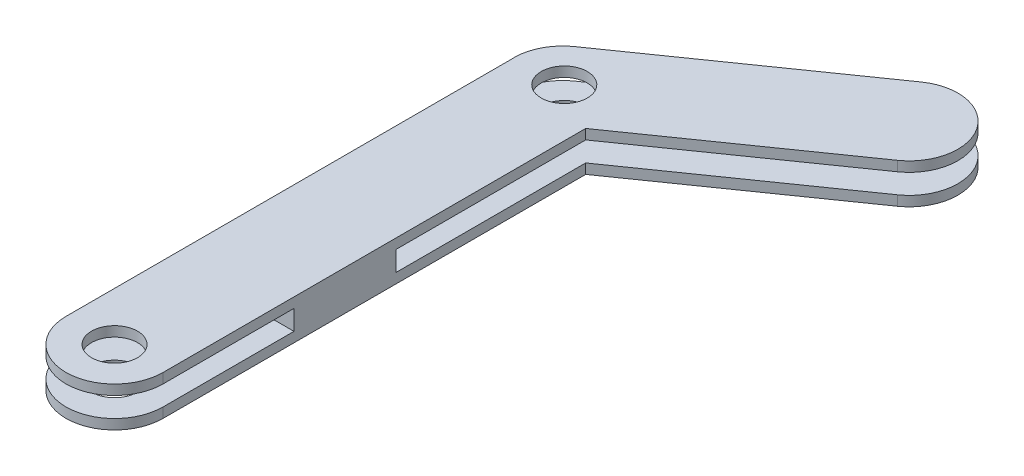
SolidWorks part; units mm, degrees
ref_plane "前视基准面" through (0, 0, 0) normal (0, 0, 1) x (1, 0, 0)
ref_plane "上视基准面" through (0, 0, 0) normal (0, 1, 0) x (1, 0, 0)
ref_plane "右视基准面" through (0, 0, 0) normal (1, 0, 0) x (0, 0, -1)
other "Configuration Table"
sketch "草图2" plane through (0, 0, 0) normal (0, 1, 0) x (1, 0, 0)
  line L0 (0, 0) -> (0, 180) construction
  line L1 (-19.5, 0) -> (-19.5, 180)
  line L2 (19.5, 0) -> (19.5, 180)
  arc A0 (-19.5, 0) -> (19.5, 0) centre (0, 0) ccw
  arc A1 (19.5, 180) -> (-19.5, 180) centre (0, 180) ccw
  point P3 (0, 90)
  dimension "D1" = 180
extrude "凸台-拉伸1" add sketch "草图2" along normal blind 4
sketch "草图3" plane through (0, 4, 0) normal (0, 1, 0) x (-1, 0, 0)
  line L0 (0, 0) -> (0, -180) construction
  circle A0 centre (0, -180) radius 9.2428
  circle A1 centre (0, 0) radius 9.2428
extrude "切除-拉伸2" cut sketch "草图3" against normal blind 8
sketch "草图5" plane through (0, 0, 0) normal (0, 1, 0) x (1, 0, 0)
  line L0 (-19.5, 180) -> (-19.5, 0) construction
  line L1 (-19.5, 93.4928) -> (19.5, 93.4928)
  line L2 (-19.5, 93.4928) -> (-19.5, 52.5871)
  line L3 (-19.5, 52.5871) -> (19.5, 52.5871)
  line L4 (19.5, 93.4928) -> (19.5, 52.5871)
  line L5 (-19.5, 93.4928) -> (19.5, 52.5871) construction
  line L6 (-19.5, 52.5871) -> (19.5, 93.4928) construction
  line L7 (19.5, 0) -> (19.5, 180) construction
  point P0 (0, 73.0399)
extrude "凸台-拉伸2" add sketch "草图5" against normal blind 4
ref_plane "基准面2" through (0, -4, 0) normal (0, -1, 0) x (1, 0, 0)
mirror "镜向3" about plane through (0, -4, 0) normal (0, -1, 0) of "凸台-拉伸1", "切除-拉伸2", "凸台-拉伸2"
sketch "草图7" plane through (0, -12, 0) normal (0, -1, 0) x (1, 0, 0)
  line L0 (0, 0) -> (0, -180) construction
  line L1 (0, -180) -> (81.9503, -237.3076) construction
  line L2 (11.2057, -163.9758) -> (93.1559, -221.2834)
  line L3 (-11.2057, -196.0242) -> (70.7446, -253.3318)
  arc A0 (11.2057, -163.9758) -> (-11.2057, -196.0242) centre (0, -180) ccw
  arc A1 (70.7446, -253.3318) -> (93.1559, -221.2834) centre (81.9503, -237.3076) ccw
  point P4 (40.9751, -208.6538)
  dimension "D1" = 100
extrude "凸台-拉伸3" add sketch "草图7" against normal blind 4
sketch "草图8" plane through (0, -12, 0) normal (0, -1, 0) x (1, 0, 0)
  circle A0 centre (0, -180.6675) radius 9.245
  dimension "D1" = 18.49
extrude "切除-拉伸3" cut sketch "草图8" against normal blind 4
mirror "镜向6" about plane through (0, -4, 0) normal (0, -1, 0) of "切除-拉伸3", "凸台-拉伸3"
sketch "草图9" plane through (0, -12, 0) normal (0, -1, 0) x (-1, 0, 0)
  line L0 (0, 180.6675) -> (-85.9642, 240.8298) construction
  line L1 (0, 180.6675) -> (0, 0) construction
sketch "草图10" plane through (0, 4, 0) normal (0, 1, 0) x (1, 0, 0)
  line L0 (0, 180.6675) -> (0, 0) construction
